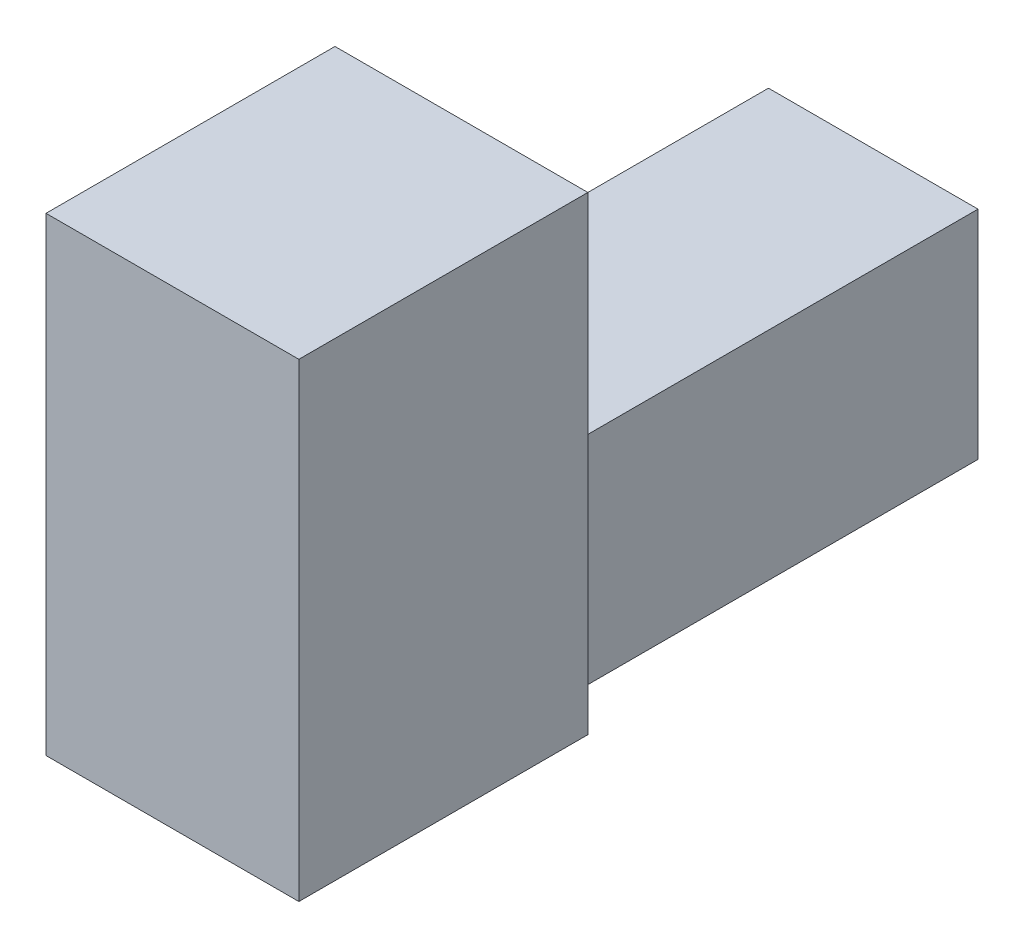
SolidWorks part; units mm, degrees
ref_plane "Front Plane" through (0, 0, 0) normal (0, 0, 1) x (1, 0, 0)
ref_plane "Top Plane" through (0, 0, 0) normal (0, 1, 0) x (1, 0, 0)
ref_plane "Right Plane" through (0, 0, 0) normal (1, 0, 0) x (0, 0, -1)
sketch "Sketch1" plane through (0, 0, 0) normal (1, 0, 0) x (0, 0, -1)
  line L1 (-50, 32.5) -> (50, 32.5)
  line L2 (-50, 32.5) -> (-50, -32.5)
  line L3 (-50, -32.5) -> (50, -32.5)
  line L4 (50, 32.5) -> (50, -32.5)
  line L5 (-50, 32.5) -> (50, -32.5) construction
  line L6 (-50, -32.5) -> (50, 32.5) construction
  point P0 (0, 0)
  dimension "D1" = 100
  dimension "D2" = 65
extrude "Boss-Extrude1" add sketch "Sketch1" along normal blind 35
sketch "Sketch4" plane through (35, 0, 0) normal (1, 0, 0) x (0, 0, -1)
  line L0 (50, -32.5) -> (50, 32.5) construction
  line L1 (50, -32.5) -> (-10, -32.5)
  line L2 (50, -32.5) -> (50, -2.5)
  line L3 (50, -2.5) -> (-10, -2.5)
  line L4 (-10, -32.5) -> (-10, -2.5)
  line L5 (-50, -32.5) -> (50, -32.5) construction
  dimension "D1" = 60
  dimension "D2" = 30
extrude "Cut-Extrude1" cut sketch "Sketch4" against normal blind 6
sketch "Sketch5" plane through (35, 0, 0) normal (1, 0, 0) x (0, 0, -1)
  line L0 (50, -2.5) -> (50, 32.5) construction
  line L1 (50, 32.5) -> (-10, 32.5)
  line L2 (50, 32.5) -> (50, -2.5)
  line L3 (50, -2.5) -> (-10, -2.5)
  line L4 (-10, 32.5) -> (-10, -2.5)
  line L5 (50, -2.5) -> (-10, -2.5) construction
  line L6 (50, 32.5) -> (-50, 32.5) construction
  line L7 (-10, -2.5) -> (-10, -32.5) construction
extrude "Cut-Extrude2" cut sketch "Sketch5" against normal through all
